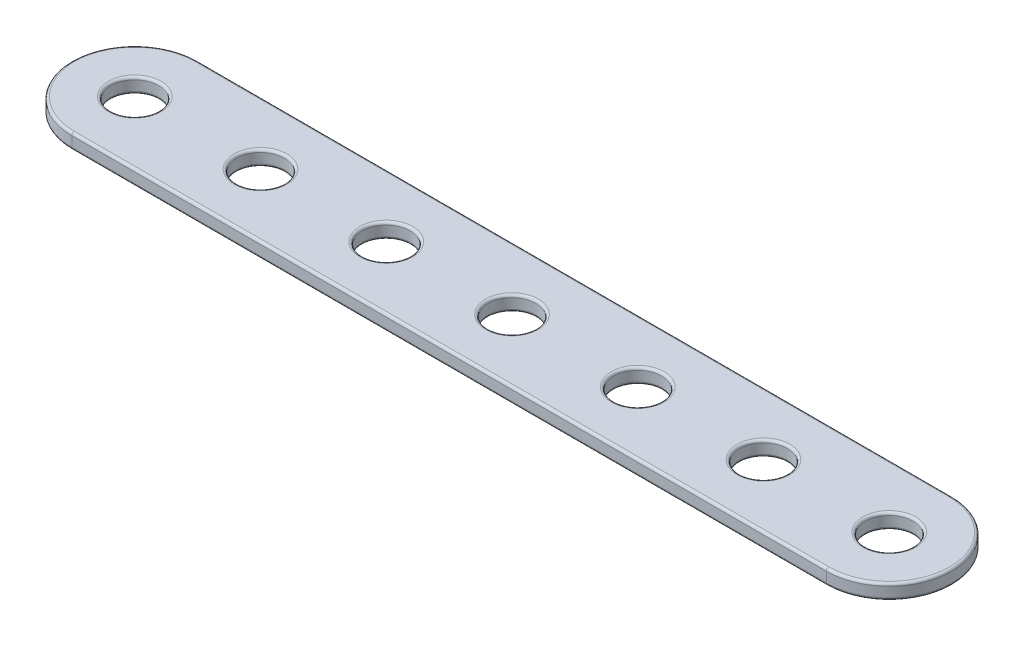
SolidWorks part; units mm, degrees
material "AISI 304"
ref_plane "Front" through (0, 0, 0) normal (0, 0, 1) x (1, 0, 0)
ref_plane "Top" through (0, 0, 0) normal (0, 1, 0) x (1, 0, 0)
ref_plane "Right" through (0, 0, 0) normal (1, 0, 0) x (0, 0, -1)
sketch "Sketch1" plane through (0, 0, 0) normal (0, 1, 0) x (1, 0, 0)
  line L1 (0, 0) -> (76.2, 0)
  line L3 (0, 12.7) -> (76.2, 12.7)
  arc A0 (0, 12.7) -> (0, 0) centre (0, 6.35) ccw
  arc A1 (76.2, 0) -> (76.2, 12.7) centre (76.2, 6.35) ccw
  dimension "D1" = 12.7
  dimension "D2" = 76.2
extrude "Extrude1" add sketch "Sketch1" along normal blind 1.524
sketch "Sketch2" plane through (0, 1.524, 0) normal (0, 1, 0) x (-1, 0, 0)
  line L0 (-76.2, -12.7) -> (0, -12.7) construction
  circle A0 centre (0, -6.35) radius 2.413
  dimension "D2" = 4.826
  dimension "D1" = 6.35
extrude "Cut-Extrude1" cut sketch "Sketch2" against normal through all
pattern_linear "LPattern1" count 7 spacing 12.7 along (1, 0, 0) of "Cut-Extrude1"
fillet "Fillet1" radius 0.254 22 edges at (38.1, 0, 0) (82.55, 0, -6.35) (38.1, 0, -12.7) (-6.35, 0, -6.35) (0, 0, -3.937) (12.7, 0, -3.937) (25.4, 0, -3.937) (38.1, 0, -3.937) (50.8, 0, -3.937) (63.5, 0, -3.937) (76.2, 0, -3.937) (38.1, 1.524, -12.7) (82.55, 1.524, -6.35) (38.1, 1.524, 0) (-6.35, 1.524, -6.35) (0, 1.524, -3.937) (12.7, 1.524, -3.937) (25.4, 1.524, -3.937) (38.1, 1.524, -3.937) (50.8, 1.524, -3.937) (63.5, 1.524, -3.937) (76.2, 1.524, -3.937)
equation "\"D2@Sketch1\" = \"D3@LPattern1\" *  ( \"D1@LPattern1\" - 1 ) "
